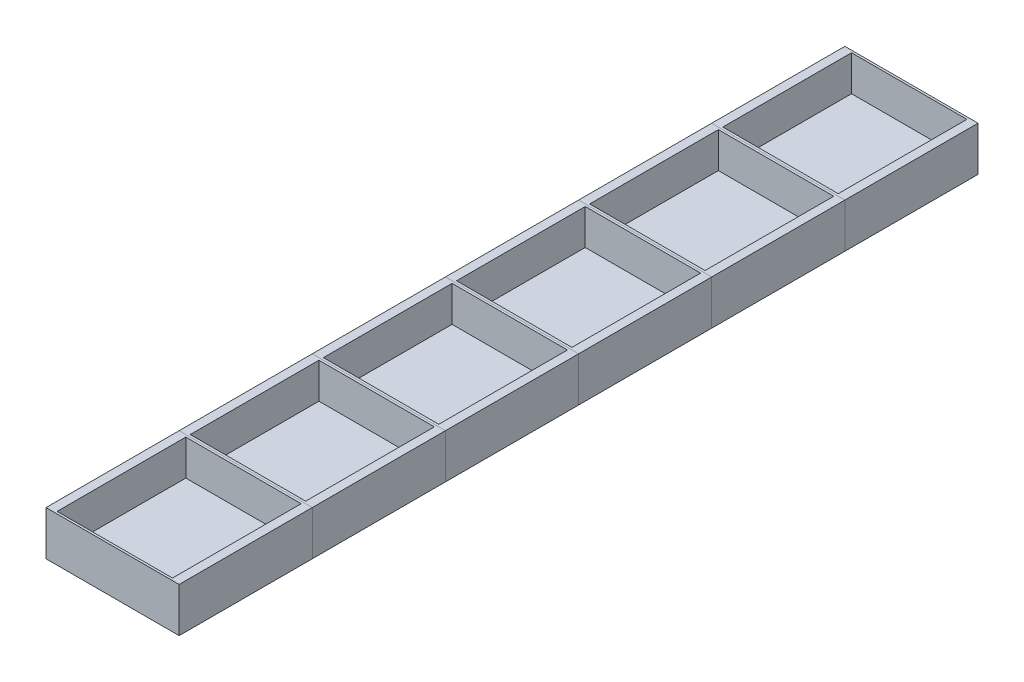
SolidWorks part; units mm, degrees
ref_plane "Front Plane" through (0, 0, 0) normal (0, 0, 1) x (1, 0, 0)
ref_plane "Top Plane" through (0, 0, 0) normal (0, 1, 0) x (1, 0, 0)
ref_plane "Right Plane" through (0, 0, 0) normal (1, 0, 0) x (0, 0, -1)
sketch "Sketch1" plane through (0, 0, 0) normal (0, 1, 0) x (1, 0, 0)
  line L0 (0, 75) -> (0, -37.4134) construction
  line L1 (-75, 0) -> (75, 0)
  line L2 (-75, 0) -> (-75, 150)
  line L3 (-75, 150) -> (75, 150)
  line L4 (75, 0) -> (75, 150)
  line L5 (-75, 0) -> (75, 150) construction
  line L6 (-75, 150) -> (75, 0) construction
  point P0 (0, 0)
  point P10 (0, 0)
  dimension "D1" = 150
  dimension "D2" = 150
extrude "Boss-Extrude1" add sketch "Sketch1" along normal blind 50
sketch "Sketch2" plane through (0, 50, 0) normal (0, 1, 0) x (1, 0, 0)
  line L0 (-75, 0) -> (75, 0) construction
  line L1 (-65, 2.5) -> (65, 2.5)
  line L2 (-65, 2.5) -> (-65, 147.5)
  line L3 (-65, 147.5) -> (65, 147.5)
  line L4 (65, 2.5) -> (65, 147.5)
  line L5 (-65, 2.5) -> (65, 147.5) construction
  line L6 (-65, 147.5) -> (65, 2.5) construction
  line L7 (75, 150) -> (-75, 150) construction
  line L8 (75, 0) -> (75, 150) construction
  line L9 (-75, 150) -> (-75, 0) construction
  point P0 (0, 75)
  dimension "D1" = 2.5
  dimension "D2" = 2.5
  dimension "D3" = 10
  dimension "D4" = 10
extrude "Cut-Extrude1" cut sketch "Sketch2" against normal blind 40
sketch "Sketch3" plane through (0, 0, 0) normal (0, 1, 0) x (1, 0, 0)
  line L0 (0, 0) -> (0, 96.1036) construction
pattern_linear "LPattern9" count 6 spacing 150 along (0, 0, -1) of bodies 112
sketch "Sketch4" plane through (0, 10, 0) normal (0, 1, 0) x (1, 0, 0)
  line L4 (65, 752.5) -> (65, 897.5)
  line L5 (65, 752.5) -> (65, 897.5)
  line L6 (65, 897.5) -> (-65, 897.5)
  line L7 (65, 897.5) -> (-65, 897.5)
  line L13 (-65, 897.5) -> (-65, 752.5)
  line L14 (-65, 897.5) -> (-65, 752.5)
  line L15 (-65, 752.5) -> (65, 752.5)
  line L16 (-65, 752.5) -> (65, 752.5)
  dimension "D1" = 0
